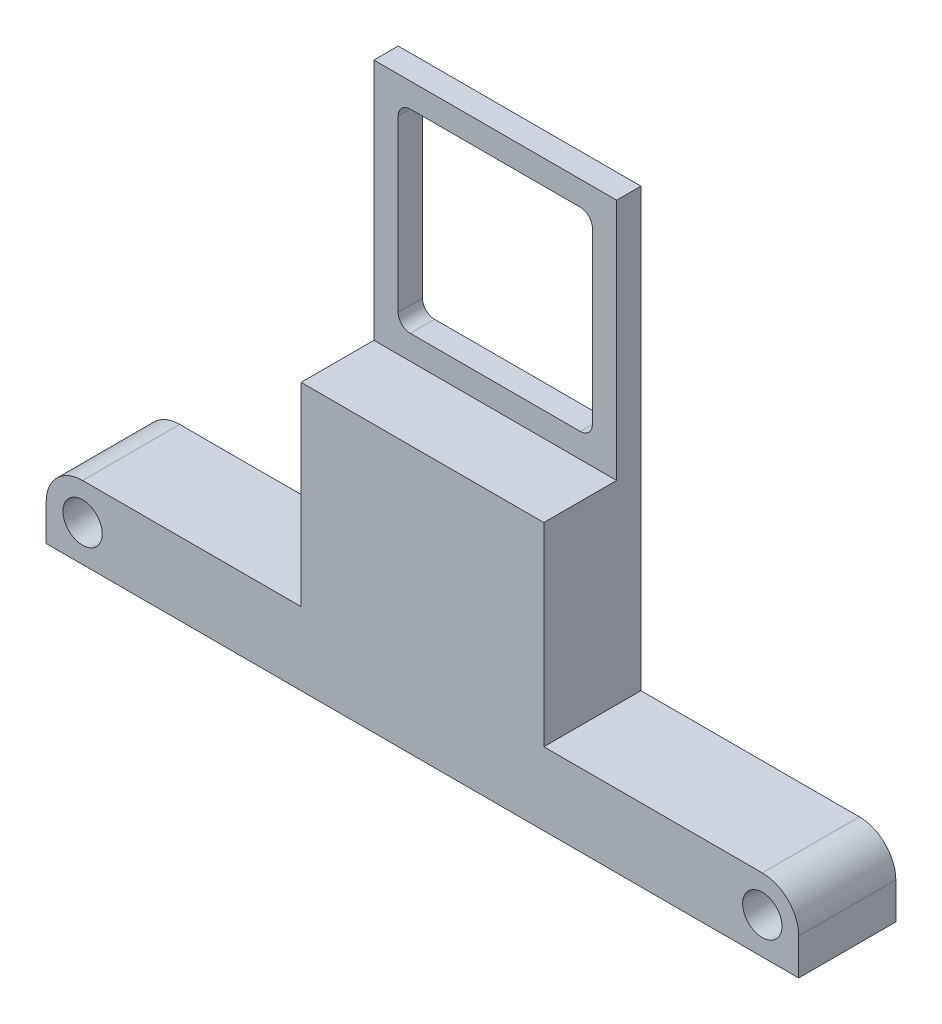
SolidWorks part; units mm, degrees
material "ABS"
ref_plane "Front Plane" through (0, 0, 0) normal (0, 0, 1) x (1, 0, 0)
ref_plane "Top Plane" through (0, 0, 0) normal (0, 1, 0) x (1, 0, 0)
ref_plane "Right Plane" through (0, 0, 0) normal (1, 0, 0) x (0, 0, -1)
sketch "Sketch1" plane through (0, 0, 0) normal (0, 0, 1) x (1, 0, 0)
  line L0 (-77.5, 0) -> (77.5, 0)
  line L1 (-70, 7.5) -> (70, 7.5) construction
  line L2 (-77.5, 0) -> (-77.5, 7.5)
  line L3 (-70, 15) -> (-25, 15)
  line L4 (-25, 15) -> (-25, 105)
  line L5 (-25, 105) -> (25, 105)
  line L6 (25, 105) -> (25, 15)
  line L7 (25, 15) -> (70, 15)
  line L8 (77.5, 7.5) -> (77.5, 0)
  circle A0 centre (-70, 7.5) radius 4.05
  circle A1 centre (70, 7.5) radius 4.05
  arc A2 (-77.5, 7.5) -> (-70, 15) centre (-70, 7.5) cw
  arc A3 (70, 15) -> (77.5, 7.5) centre (70, 7.5) cw
  point P2 (0, 0)
  point P6 (0, 105)
  point P8 (0, 7.5)
  dimension "D2" = 8.1
  dimension "D1" = 140
  dimension "D3" = 155
  dimension "D4" = 7.5
  dimension "D5" = 90
  dimension "D6" = 50
extrude "Boss-Extrude1" add sketch "Sketch1" along normal mid plane 20 contours L4 L5 L6 L7 A3 L8 L0 L2 A2 L3
sketch "Sketch3" plane through (0, 0, 10) normal (0, 0, 1) x (1, 0, 0)
  line L0 (25, 15) -> (25, 105) construction
  line L1 (-25, 105) -> (25, 105)
  line L2 (-25, 105) -> (-25, 55)
  line L3 (-25, 55) -> (25, 55)
  line L4 (25, 105) -> (25, 55)
extrude "Cut-Extrude2" cut sketch "Sketch3" against normal blind 15
sketch "Sketch4" plane through (0, 0, -5) normal (0, 0, 1) x (1, 0, 0)
  line L0 (-25, 55) -> (25, 55) construction
  line L1 (-20, 100) -> (20, 100)
  line L2 (-20, 100) -> (-20, 60)
  line L3 (-20, 60) -> (20, 60)
  line L4 (20, 100) -> (20, 60)
  line L5 (-25, 105) -> (-25, 55) construction
  point P6 (0, 55)
  point P7 (0, 60)
  point P8 (-20, 80)
  point P11 (-25, 80)
  dimension "D1" = 40
extrude "Cut-Extrude3" cut sketch "Sketch4" against normal through all
fillet "Fillet1" radius 2.5 4 edges at (20, 100, -7.5) (20, 60, -7.5) (-20, 100, -7.5) (-20, 60, -7.5)
